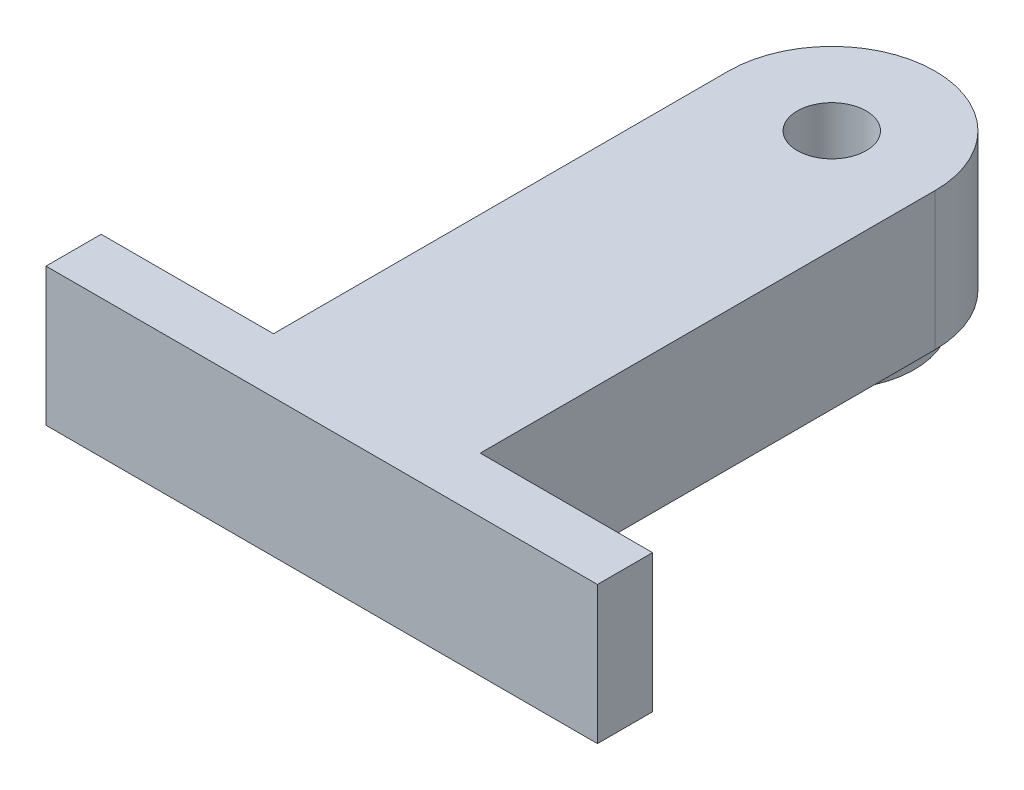
SolidWorks part; units mm, degrees
ref_plane "Alzado" through (0, 0, 0) normal (0, 0, 1) x (1, 0, 0)
ref_plane "Planta" through (0, 0, 0) normal (0, 1, 0) x (1, 0, 0)
ref_plane "Vista lateral" through (0, 0, 0) normal (1, 0, 0) x (0, 0, -1)
sketch "Croquis2" plane through (0, 0, 0) normal (0, 1, 0) x (1, 0, 0)
  line L0 (-275, 40) -> (-275, 345)
  line L1 (0, 0) -> (-400, 0)
  line L2 (0, 0) -> (0, 40)
  line L3 (0, 40) -> (-400, 40)
  line L4 (-400, 0) -> (-400, 40)
  line L5 (-200, 40) -> (-125, 40)
  line L8 (-125, 40) -> (-125, 345)
  line L9 (-125, 370) -> (-125, 345)
  line L10 (-275, 370) -> (-275, 345)
  circle A0 centre (-200, 370) radius 25
  circle A1 centre (-200, 370) radius 75
extrude "Saliente-Extruir1" add sketch "Croquis2" along normal blind 100 contours A1 A0 | A1 L10 L0 L3 L8 L9 | L4 L1 L2 L3
sketch "Croquis3" plane through (0, 0, 0) normal (0, -1, 0) x (-1, 0, 0)
  circle A0 centre (200, 370) radius 60
  circle A1 centre (200, 370) radius 25
extrude "Saliente-Extruir2" add sketch "Croquis3" along normal blind 20
